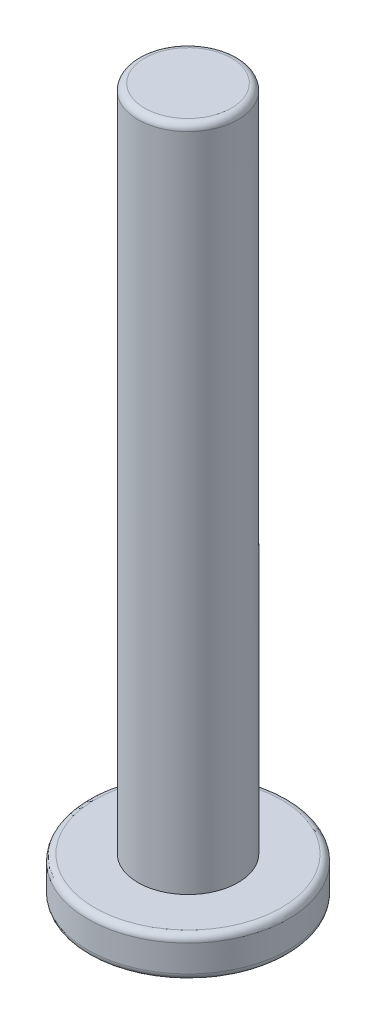
SolidWorks part; units mm, degrees
ref_plane "Front Plane" through (0, 0, 0) normal (0, 0, 1) x (1, 0, 0)
ref_plane "Top Plane" through (0, 0, 0) normal (0, 1, 0) x (1, 0, 0)
ref_plane "Right Plane" through (0, 0, 0) normal (1, 0, 0) x (0, 0, -1)
sketch "Sketch2" plane through (0, 0, 0) normal (0, 0, 1) x (1, 0, 0)
  line L0 (0, 0) -> (3, 0)
  line L1 (3, 0) -> (3, 1.2)
  line L2 (3, 1.2) -> (1.5, 1.2)
  line L3 (1.5, 1.2) -> (1.5, 21.2)
  line L4 (1.5, 21.2) -> (0, 21.2)
  line L5 (0, 21.2) -> (0, 0)
  line L6 (0, 73.1143) -> (0, -37.0787) construction
  dimension "D1" = 3
  dimension "D2" = 20
  dimension "D3" = 1.2
  dimension "D4" = 1.5
revolve "Revolve1" add sketch "Sketch2" angle 360 about L6
fillet "Fillet1" radius 0.2 3 edges at (0, 0, 3) (0, 1.2, 3) (0, 21.2, 1.5)
sketch "Sketch3" plane through (0, 0, 0) normal (0, -1, 0) x (1, 0, 0)
  line L1 (1.4434, 0) -> (0.7217, 1.25)
  line L2 (0.7217, 1.25) -> (-0.7217, 1.25)
  line L3 (-0.7217, 1.25) -> (-1.4434, 0)
  line L4 (-1.4434, 0) -> (-0.7217, -1.25)
  line L5 (-0.7217, -1.25) -> (0.7217, -1.25)
  line L6 (0.7217, -1.25) -> (1.4434, 0)
  circle A0 centre (0, 0) radius 1.25 construction
  dimension "D1" = 2.5
extrude "Cut-Extrude1" cut sketch "Sketch3" against normal blind 1
